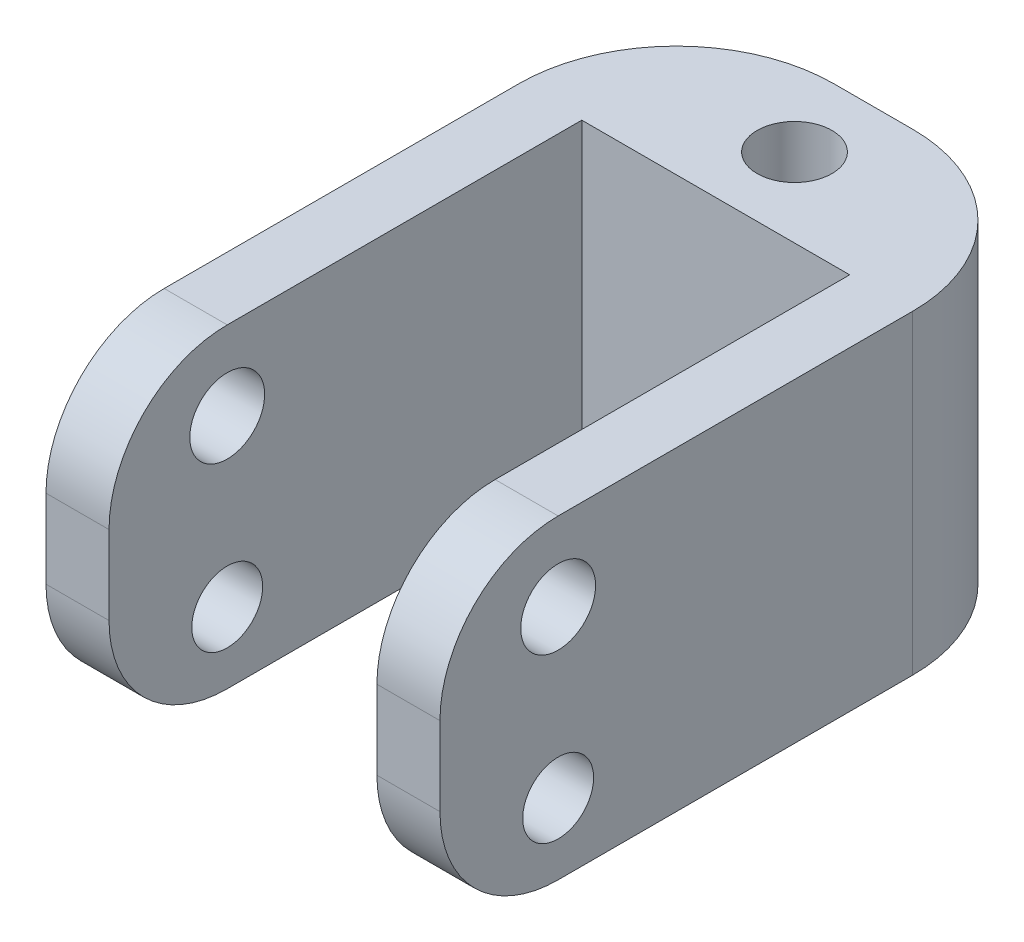
SolidWorks part; units mm, degrees
ref_plane "Front Plane" through (0, 0, 0) normal (0, 0, 1) x (1, 0, 0)
ref_plane "Top Plane" through (0, 0, 0) normal (0, 1, 0) x (1, 0, 0)
ref_plane "Right Plane" through (0, 0, 0) normal (1, 0, 0) x (0, 0, -1)
sketch "Sketch4" plane through (0, 0, 0) normal (1, 0, 0) x (0, 0, -1)
  line L0 (-25, -11) -> (-25, -20) construction
  line L1 (-40, -20) -> (40, -20)
  line L2 (-40, -20) -> (-40, 20)
  line L3 (-40, 20) -> (40, 20)
  line L4 (40, -20) -> (40, 20)
  line L5 (-40, -20) -> (40, 20) construction
  line L6 (-40, 20) -> (40, -20) construction
  line L7 (-25, 10) -> (-25, -11) construction
  circle A0 centre (-25, 10) radius 4.75
  circle A1 centre (-25, -11) radius 4.5
  circle A2 centre (-25, 10) radius 21 construction
  point P0 (0, 0)
  dimension "D3" = 9.5
  dimension "D4" = 10
  dimension "D5" = 15
  dimension "D6" = 9
  dimension "D7" = 42
  dimension "D1" = 40
  dimension "D2" = 80
extrude "Boss-Extrude2" add sketch "Sketch4" along normal mid plane 50
sketch "Sketch5" plane through (0, 0, 0) normal (0, 1, 0) x (1, 0, 0)
  line L0 (25, -40) -> (-25, -40) construction
  line L1 (-17, -40) -> (17, -40)
  line L2 (-17, -40) -> (-17, 20)
  line L3 (-17, 20) -> (17, 20)
  line L4 (17, -40) -> (17, 20)
  line L5 (0, 0) -> (0, -40) construction
  line L6 (15, -16.7956) -> (15, -59.1309) construction
  dimension "D1" = 2
  dimension "D2" = 60
extrude "Cut-Extrude3" cut sketch "Sketch5" against normal through all both and the other way through all
sketch "Sketch6" plane through (0, 0, 0) normal (0, 1, 0) x (1, 0, 0)
  line L0 (25, 40) -> (-25, 40) construction
  line L1 (0, 0) -> (0, 30) construction
  circle A0 centre (0, 30) radius 4.75
  dimension "D1" = 9.5
  dimension "D2" = 10
extrude "Cut-Extrude4" cut sketch "Sketch6" against normal through all both and the other way through all
fillet "Fillet1" radius 20 2 edges at (-25, 0, -40) (25, 0, -40)
fillet "Fillet3" radius 15 4 edges at (-21, 20, 40) (-21, -20, 40) (21, -20, 40) (21, 20, 40)
